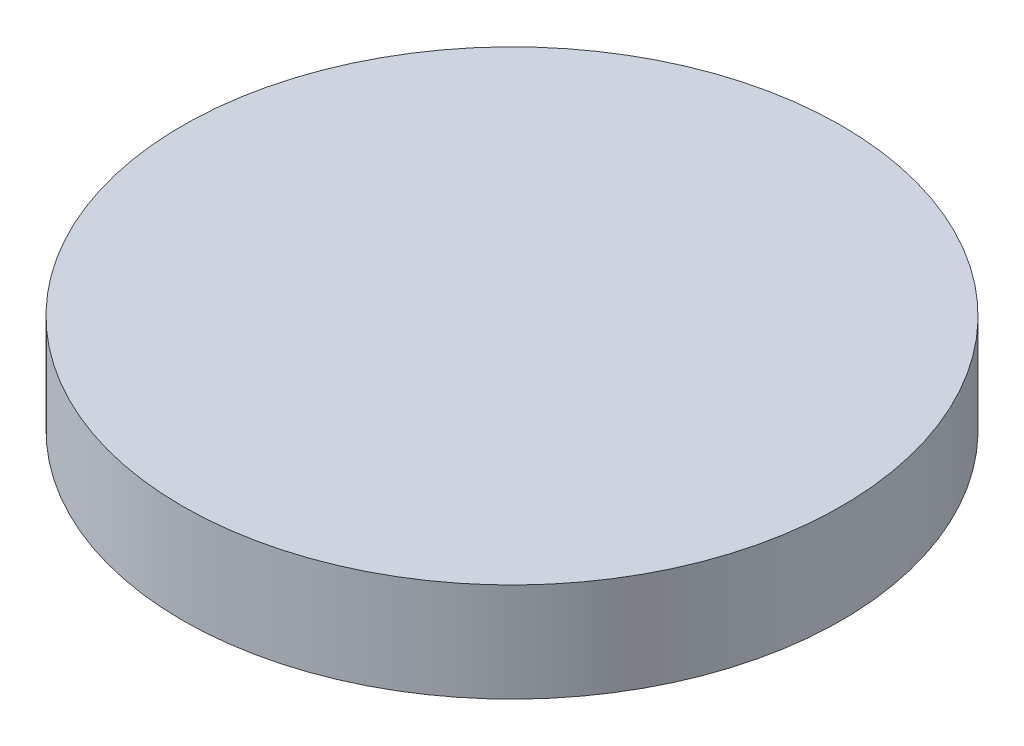
SolidWorks part; units mm, degrees
ref_plane "Plan de face" through (0, 0, 0) normal (1, 0, 0) x (0, 1, 0)
ref_plane "Plan de dessus" through (0, 0, 0) normal (0, 0, 1) x (0, 1, 0)
ref_plane "Plan de droite" through (0, 0, 0) normal (0, 1, 0) x (-1, 0, 0)
sketch "Esquisse1" plane through (0, 0, 0) normal (0, 1, 0) x (-1, 0, 0)
  circle A0 centre (0, 0) radius 5
extrude "Boss.-Extru.1" add sketch "Esquisse1" along normal blind 1.5
